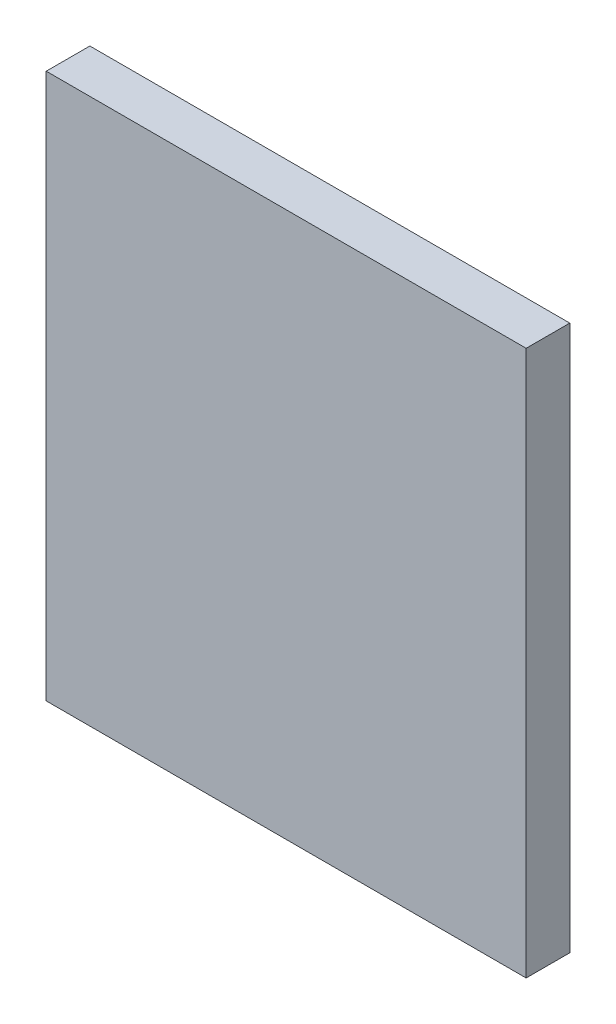
SolidWorks part; units mm, degrees
ref_plane "Front Plane" through (0, 0, 0) normal (0, 0, 1) x (1, 0, 0)
ref_plane "Top Plane" through (0, 0, 0) normal (0, 1, 0) x (1, 0, 0)
ref_plane "Right Plane" through (0, 0, 0) normal (1, 0, 0) x (0, 0, -1)
sketch "Sketch1" plane through (0, 0, 0) normal (0, 0, 1) x (1, 0, 0)
  line L1 (0, 0) -> (22, 0)
  line L2 (0, 0) -> (0, 25)
  line L3 (0, 25) -> (22, 25)
  line L4 (22, 0) -> (22, 25)
  dimension "D1" = 25
  dimension "D2" = 22
extrude "Boss-Extrude1" add sketch "Sketch1" along normal blind 2
